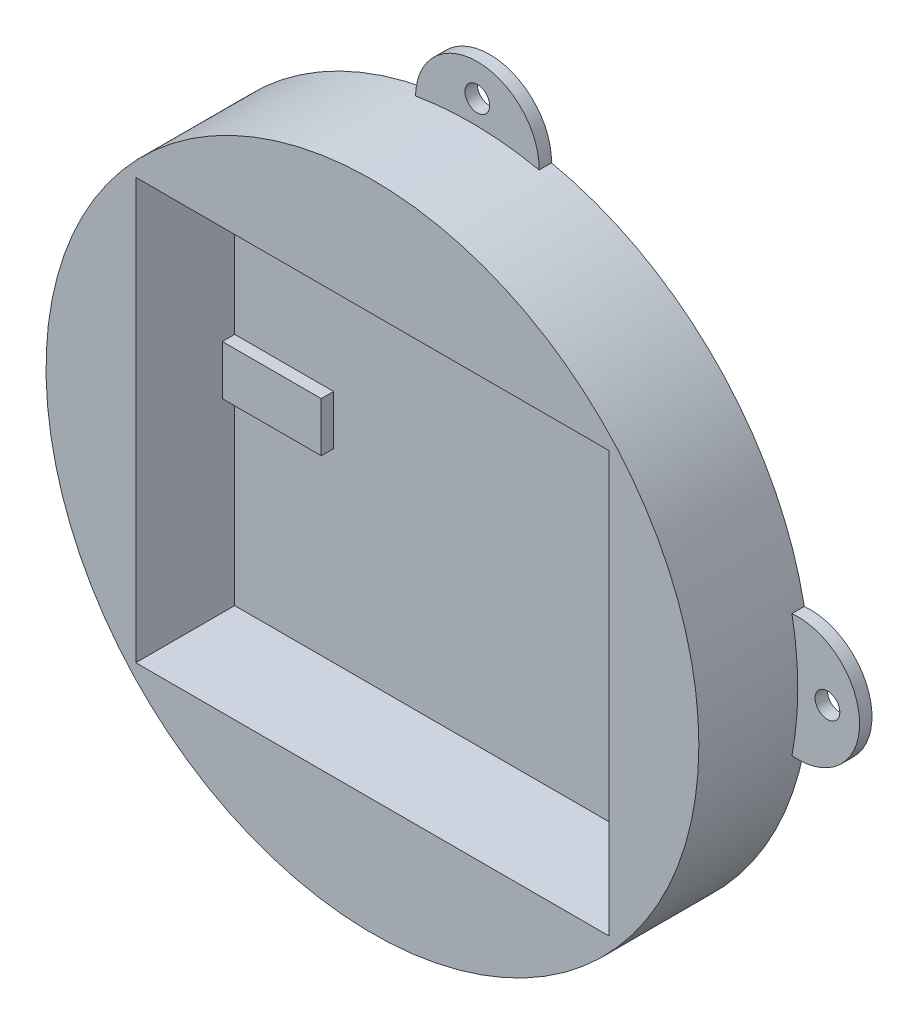
SolidWorks part; units mm, degrees
ref_plane "Front Plane" through (0, 0, 0) normal (0, 0, 1) x (1, 0, 0)
ref_plane "Top Plane" through (0, 0, 0) normal (0, 1, 0) x (1, 0, 0)
ref_plane "Right Plane" through (0, 0, 0) normal (1, 0, 0) x (0, 0, -1)
sketch "Sketch1" plane through (0, 0, 0) normal (0, 0, 1) x (1, 0, 0)
  circle A0 centre (0, 0) radius 132
extrude "Boss-Extrude1" add sketch "Sketch1" along normal blind 5
sketch "Sketch2" plane through (0, 0, 5) normal (0, 0, 1) x (1, 0, 0)
  circle A0 centre (0, 0) radius 128
  circle A1 centre (0, 0) radius 132 construction
  circle A2 centre (0, 0) radius 132
extrude "Boss-Extrude2" add sketch "Sketch2" along normal blind 40
sketch "Sketch3" plane through (0, 0, 5) normal (0, 0, 1) x (1, 0, 0)
  line L1 (-95.71, -84.9917) -> (95.71, -84.9917)
  line L2 (-95.71, -84.9917) -> (-95.71, 84.9917)
  line L3 (-95.71, 84.9917) -> (95.71, 84.9917)
  line L4 (95.71, -84.9917) -> (95.71, 84.9917)
  line L5 (-95.71, -84.9917) -> (95.71, 84.9917) construction
  line L6 (-95.71, 84.9917) -> (95.71, -84.9917) construction
  circle A0 centre (0, 0) radius 128 construction
  circle A1 centre (0, 0) radius 128
  circle M1 centre (0, 0) radius 128
extrude "Boss-Extrude3" add sketch "Sketch3" along normal blind 40 contours L3 M1 | L4 M1 | L1 M1 | L2 M1
sketch "Sketch4" plane through (95.71, 0, 0) normal (-1, 0, 0) x (0, 0, 1)
  line L0 (45, 0) -> (5, 0) construction
  line L1 (45, -84.9917) -> (45, 84.9917) construction
  line L2 (5, -84.9917) -> (5, 84.9917) construction
sketch "Sketch6" plane through (0, 0, 5) normal (0, 0, 1) x (1, 0, 0)
  line L3 (-30, -10) -> (-30, 10)
  line L5 (-30, 10) -> (-70, 10)
  line L6 (-30, 10) -> (-30, -10)
  line L7 (-30, -10) -> (-70, -10)
  line L8 (-70, 10) -> (-70, -10)
  point P12 (-30, 0)
  dimension "D1" = 40
extrude "Boss-Extrude5" add sketch "Sketch6" along normal blind 5 contours L5 L8 L7 L3
sketch "Sketch7" plane through (0, 0, 10) normal (0, 0, 1) x (1, 0, 0)
  line L1 (-70, 10) -> (-30, 10)
  line L2 (-70, 10) -> (-70, -10)
  line L3 (-70, -10) -> (-30, -10)
  line L4 (-30, 10) -> (-30, -10)
extrude "Cut-Extrude1" cut sketch "Sketch7" against normal blind 5
sketch "Sketch8" plane through (0, 0, 5) normal (0, 0, 1) x (1, 0, 0)
  line L0 (0, 0) -> (-95.71, 0)
  line L1 (-95.71, -84.9917) -> (-95.71, 84.9917) construction
  line L2 (-95.71, -10) -> (-95.71, 10)
  line L3 (-95.71, -84.9917) -> (-95.71, 84.9917) construction
  line L4 (-95.71, 10) -> (-55.71, 10)
  line L6 (-55.71, 10) -> (-95.71, 10)
  line L7 (-55.71, 10) -> (-55.71, -10)
  line L8 (-55.71, -10) -> (-95.71, -10)
  line L9 (-95.71, 10) -> (-95.71, -10)
  point P10 (-95.71, 0)
extrude "Boss-Extrude7" add sketch "Sketch8" along normal blind 5 contours L8 L7 L0 L1 | L7 L4 L1 L0
sketch "Sketch9" plane through (0, 0, 0) normal (0, 0, -1) x (-1, 0, 0)
  arc A0 (-129.6326, 24.8877) -> (-129.6326, -24.8877) centre (-132, 0) ccw
  circle A1 centre (0, 0) radius 132 construction
  circle A2 centre (-144, 0) radius 5
  circle A3 centre (0, 0) radius 132
  circle M1 centre (0, 0) radius 132
extrude "Boss-Extrude8" add sketch "Sketch9" against normal blind 5 contours A0 A2 M1
pattern_circular "CirPattern1" count 4 over 360 about axis through (2.4044, 0, 0) along (0, 0, 1) of "Boss-Extrude8"
